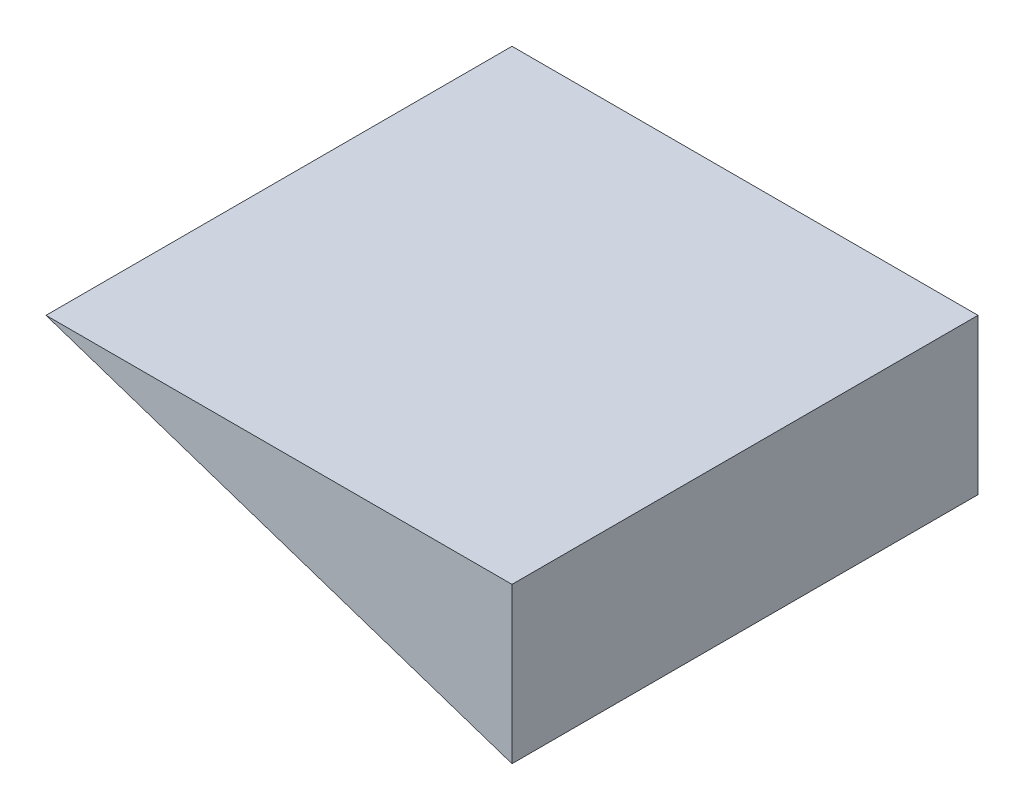
SolidWorks part; units mm, degrees
ref_plane "Front Plane" through (0, 0, 0) normal (0, 0, 1) x (1, 0, 0)
ref_plane "Top Plane" through (0, 0, 0) normal (0, 1, 0) x (1, 0, 0)
ref_plane "Right Plane" through (0, 0, 0) normal (1, 0, 0) x (0, 0, -1)
sketch "Sketch1" plane through (0, 0, 0) normal (0, 0, 1) x (1, 0, 0)
  line L1 (-150, 50) -> (150, 50)
  line L2 (-150, 50) -> (-150, -50)
  line L3 (-150, -50) -> (150, -50)
  line L4 (150, 50) -> (150, -50)
  line L5 (-150, 50) -> (150, -50) construction
  line L6 (-150, -50) -> (150, 50) construction
  point P0 (0, 0)
  dimension "D1" = 100
  dimension "D2" = 300
extrude "Boss-Extrude1" add sketch "Sketch1" against normal blind 300
sketch "Sketch2" plane through (0, 0, 0) normal (0, 0, 1) x (1, 0, 0)
  line L0 (-150, 50) -> (-150, -50)
  line L1 (-150, -50) -> (150, -50)
  line L2 (150, -50) -> (-150, 50)
sketch "Sketch3" plane through (-150, 0, 0) normal (-1, 0, 0) x (0, 0, 1)
  line L0 (-300, -50) -> (0, -50) construction
  line L1 (-6, -50) -> (-294, -50)
  line L2 (-6, -50) -> (-6, 44)
  line L3 (-6, 44) -> (-294, 44)
  line L4 (-294, -50) -> (-294, 44)
  line L5 (-300, 50) -> (0, 50) construction
  line L6 (-300, 50) -> (-300, -50) construction
  line L7 (0, -50) -> (0, 50) construction
  dimension "D1" = 6
  dimension "D2" = 6
  dimension "D3" = 6
extrude "Cut-Extrude2" cut sketch "Sketch3" against normal blind 294
extrude "Cut-Extrude3" cut sketch "Sketch2" against normal blind 316
scale "Scale1" scale about centroid uniform scaling yes scale factor 0.001
